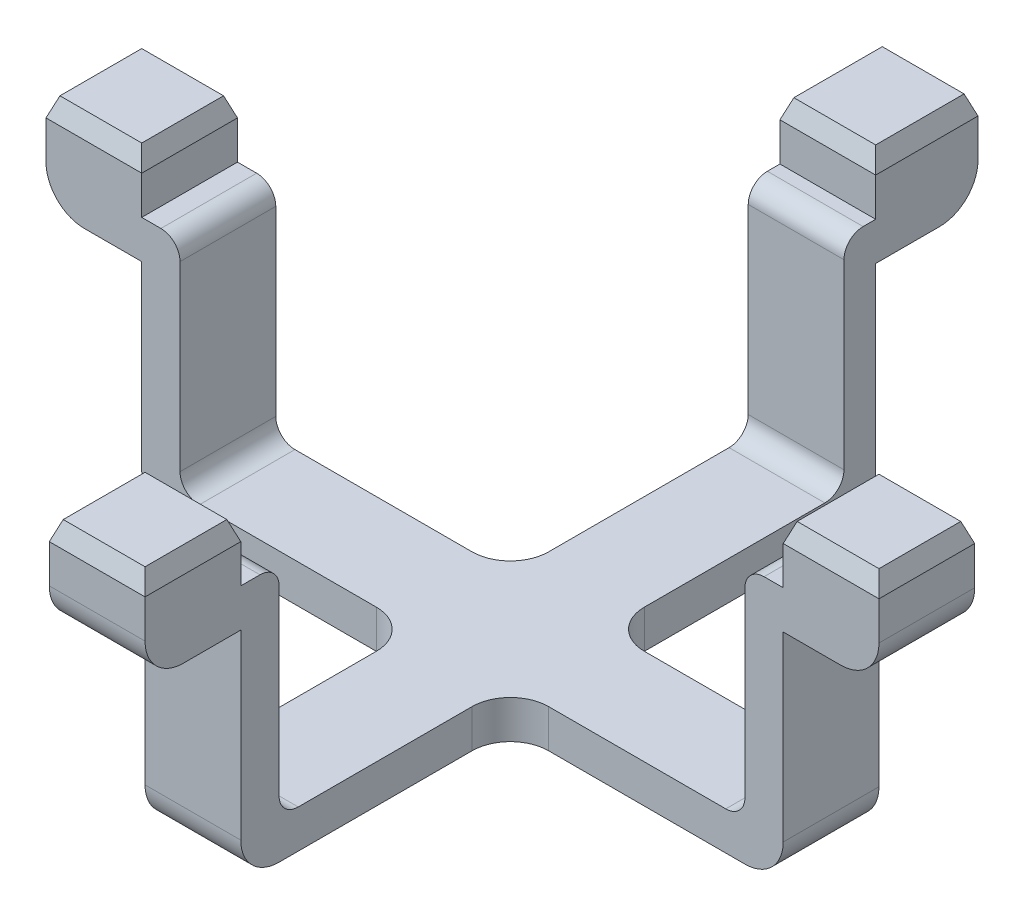
SolidWorks part; units mm, degrees
ref_plane "Front Plane" through (0, 0, 0) normal (0, 0, 1) x (1, 0, 0)
ref_plane "Top Plane" through (0, 0, 0) normal (0, 1, 0) x (1, 0, 0)
ref_plane "Right Plane" through (0, 0, 0) normal (1, 0, 0) x (0, 0, -1)
sketch "Sketch1" plane through (0, 0, 0) normal (0, 0, 1) x (1, 0, 0)
  line L0 (16.75, 0) -> (-16.75, 0)
  line L1 (-16.75, 0) -> (-16.75, 11.5)
  line L2 (-16.75, 11.5) -> (-21.75, 11.5)
  line L3 (-21.75, 11.5) -> (-21.75, 13.5)
  line L4 (-21.75, 13.5) -> (-14.75, 13.5)
  line L7 (-14.75, 13.5) -> (-14.75, 2)
  line L8 (-14.75, 2) -> (14.75, 2)
  line L9 (14.75, 2) -> (14.75, 13.5)
  line L12 (14.75, 13.5) -> (21.75, 13.5)
  line L13 (21.75, 13.5) -> (21.75, 11.5)
  line L14 (21.75, 11.5) -> (16.75, 11.5)
  line L15 (16.75, 11.5) -> (16.75, 0)
  point P0 (14.75, 6.571)
  point P4 (0, 0)
  dimension "D1" = 29.5
  dimension "D2" = 2
  dimension "D3" = 2
  dimension "D4" = 2
  dimension "D5" = 11.5
  dimension "D6" = 7
  dimension "D7" = 7
  dimension "D8" = 2
extrude "Boss-Extrude1" add sketch "Sketch1" against normal blind 5
sketch "Sketch5" plane through (0, 0, 0) normal (1, 0, 0) x (0, 0, -1)
  line L0 (19.0781, 0) -> (-14.0781, 0)
  line L1 (-14.0781, 0) -> (-14.0781, 11.5)
  line L2 (-14.0781, 11.5) -> (-19.0781, 11.5)
  line L3 (-19.0781, 11.5) -> (-19.0781, 13.5)
  line L4 (-19.0781, 13.5) -> (-12.0781, 13.5)
  line L5 (-12.0781, 13.5) -> (-12.0781, 2)
  line L6 (-12.0781, 2) -> (17.4219, 2)
  line L7 (17.4219, 2) -> (17.4219, 13.5)
  line L8 (17.4219, 13.5) -> (24.4219, 13.5)
  line L9 (24.4219, 13.5) -> (24.4219, 11.5)
  line L10 (24.4219, 11.5) -> (19.0781, 11.5)
  line L11 (19.0781, 11.5) -> (19.0781, 0)
  line L12 (5, 0) -> (0, 0) construction
  point P2 (2.5, 0)
  point P15 (2.5, 0)
  point P16 (0, 0)
  point P17 (0, 0)
  dimension "D1" = 7
  dimension "D2" = 11.5
  dimension "D3" = 2
  dimension "D4" = 33.1561
  dimension "D5" = 29.5
extrude "Boss-Extrude2" add sketch "Sketch5" along normal blind 2.5 and the other way blind 2.5
sketch "Sketch6" plane through (0, 13.5, 0) normal (0, 1, 0) x (1, 0, 0)
  line L0 (21.75, 0) -> (16.75, 0) construction
  line L1 (16.75, 0) -> (16.75, 5) construction
  line L2 (16.75, 5) -> (21.75, 5) construction
  line L3 (21.75, 5) -> (21.75, 0) construction
  line L4 (-2.5, -14.0781) -> (2.5, -14.0781) construction
  line L5 (2.5, -14.0781) -> (2.5, -19.0781) construction
  line L6 (2.5, -19.0781) -> (-2.5, -19.0781) construction
  line L7 (-2.5, -19.0781) -> (-2.5, -14.0781) construction
  line L8 (-16.75, 0) -> (-21.75, 0) construction
  line L9 (-21.75, 0) -> (-21.75, 5) construction
  line L10 (-21.75, 5) -> (-16.75, 5) construction
  line L11 (-16.75, 5) -> (-16.75, 0) construction
  line L12 (-2.5, 24.4219) -> (2.5, 24.4219) construction
  line L13 (2.5, 24.4219) -> (2.5, 19.0781) construction
  line L14 (2.5, 19.0781) -> (-2.5, 19.0781) construction
  line L15 (-2.5, 19.0781) -> (-2.5, 24.4219) construction
  line L16 (21.75, 0) -> (16.75, 0)
  line L17 (16.75, 0) -> (16.75, 5)
  line L18 (16.75, 5) -> (21.75, 5)
  line L19 (21.75, 5) -> (21.75, 0)
  line L20 (-2.5, -14.0781) -> (2.5, -14.0781)
  line L21 (2.5, -14.0781) -> (2.5, -19.0781)
  line L22 (2.5, -19.0781) -> (-2.5, -19.0781)
  line L23 (-2.5, -19.0781) -> (-2.5, -14.0781)
  line L24 (-16.75, 0) -> (-21.75, 0)
  line L25 (-21.75, 0) -> (-21.75, 5)
  line L26 (-21.75, 5) -> (-16.75, 5)
  line L27 (-16.75, 5) -> (-16.75, 0)
  line L28 (-2.5, 24.4219) -> (2.5, 24.4219)
  line L29 (2.5, 24.4219) -> (2.5, 19.0781)
  line L30 (2.5, 19.0781) -> (-2.5, 19.0781)
  line L31 (-2.5, 19.0781) -> (-2.5, 24.4219)
extrude "Boss-Extrude3" add sketch "Sketch6" along normal blind 3
fillet "Fillet1" radius 1 4 edges at (14.75, 2, -2.5) (-14.75, 2, -2.5) (0, 2, 12.0781) (0, 2, -17.4219)
fillet "Fillet2" radius 2 12 edges at (-2.5, 1, -5) (-2.5, 1, 0) (2.5, 1, 0) (2.5, 1, -5) (21.75, 11.5, -2.5) (0, 11.5, -24.4219) (-21.75, 11.5, -2.5) (0, 11.5, 19.0781) (0, 0, 14.0781) (-16.75, 0, -2.5) (0, 0, -19.0781) (16.75, 0, -2.5)
chamfer "Chamfer1" distance 1 angle 20 16 edges at (0, 16.5, 14.0781) (2.5, 16.5, 16.5781) (0, 16.5, 19.0781) (-2.5, 16.5, 16.5781) (19.25, 16.5, 0) (16.75, 16.5, -2.5) (19.25, 16.5, -5) (21.75, 16.5, -2.5) (0, 16.5, -24.4219) (2.5, 16.5, -21.75) (0, 16.5, -19.0781) (-2.5, 16.5, -21.75) (-19.25, 16.5, 0) (-21.75, 16.5, -2.5) (-19.25, 16.5, -5) (-16.75, 16.5, -2.5)
fillet "Fillet3" radius 1 4 edges at (0, 13.5, 12.0781) (14.75, 13.5, -2.5) (0, 13.5, -17.4219) (-14.75, 13.5, -2.5)
